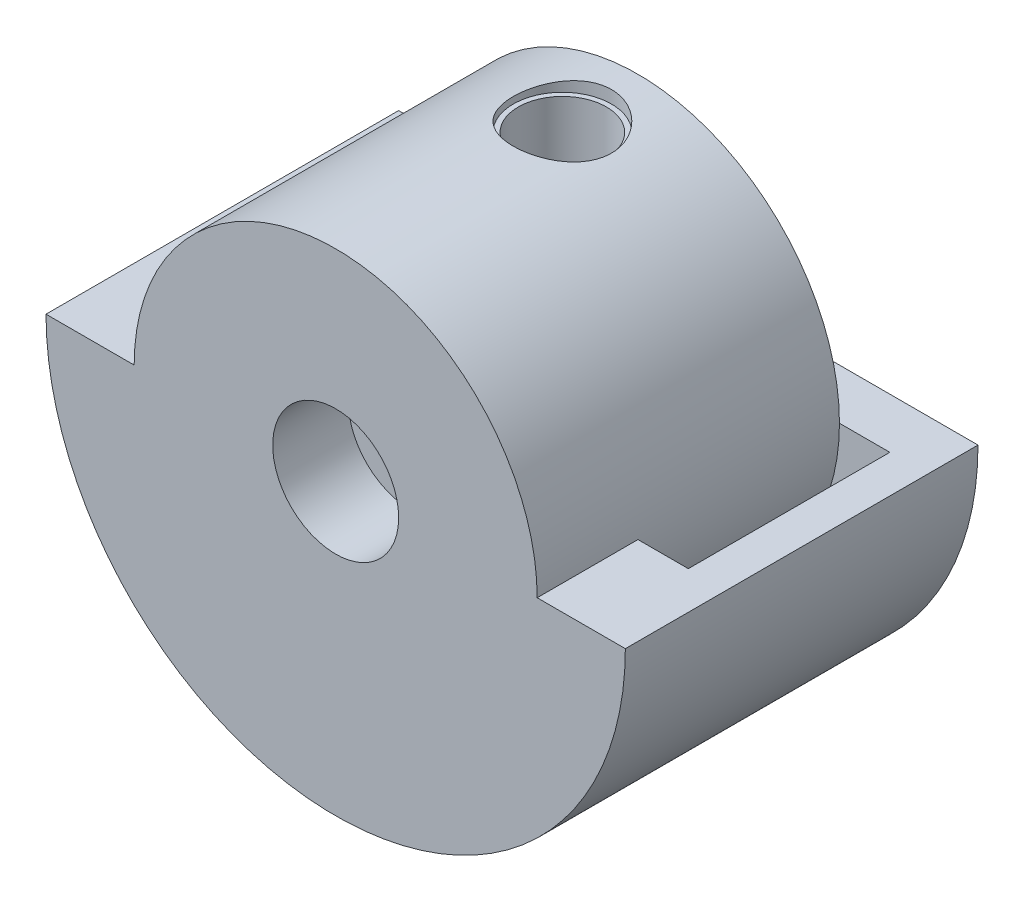
SolidWorks part; units mm, degrees
ref_plane "前视基准面" through (0, 0, 0) normal (0, 0, 1) x (1, 0, 0)
ref_plane "上视基准面" through (0, 0, 0) normal (0, 1, 0) x (1, 0, 0)
ref_plane "右视基准面" through (0, 0, 0) normal (1, 0, 0) x (0, 0, -1)
other "边界框"
ref_plane "Default Plane" through (-0.187, -7.4977, 0) normal (-0.6982, 0.7159, 0) x (0.7159, 0.6982, 0)
other "Configuration Table"
sketch "草图1" plane through (0, 0, 0) normal (0, 0, 1) x (1, 0, 0)
  line L0 (0, 0) -> (0.7723, 0) construction
  line L1 (0, 0) -> (0, 1.0561) construction
  circle A0 centre (0, 0) radius 2.5
  circle A1 centre (0, 0) radius 5
  dimension "D1" = 5
  dimension "D2" = 10
extrude "凸台-拉伸1" add sketch "草图1" along normal blind 6
sketch "草图2" plane through (0, 0, 0) normal (0, 0, 1) x (1, 0, 0)
  circle A0 centre (0, 0) radius 2.5 construction
  circle A1 centre (0, 0) radius 2.5
extrude "凸台-拉伸2" add sketch "草图2" along normal blind 3
sketch "草图3" plane through (0, 0, 0) normal (0, 0, 1) x (1, 0, 0)
  circle A0 centre (0, 0) radius 1.25
  dimension "D1" = 2.5
extrude "切除-拉伸3" cut sketch "草图3" along normal through all
sketch "草图8" plane through (0, 0, 6) normal (0, 0, 1) x (1, 0, 0)
  line L0 (-1016, 0) -> (-8, 0) construction
  line L1 (0, 0) -> (0, 7.0639) construction
  line L3 (8, 0) -> (1008.5412, 0) construction
  line L4 (-5, 0) -> (5, 0) construction
  circle A0 centre (0, 0) radius 8
  circle A1 centre (0, 0) radius 5 construction
  circle A2 centre (0, 0) radius 5
  dimension "D1" = 16
extrude "凸台-拉伸4" add sketch "草图8" against normal blind 12
ref_plane "基准面1" through (0, 8, 0) normal (0, 1, 0) x (1, 0, 0)
sketch "草图11" plane through (0, 8, 0) normal (0, 1, 0) x (1, 0, 0)
  line L0 (8, 6) -> (-8, 6) construction
  line L1 (0, 3.0864) -> (0, -9.1926) construction
  circle A0 centre (0, 3) radius 1.75
  dimension "D1" = 3.5
  dimension "D2" = 3
extrude "切除-拉伸4" cut sketch "草图11" against normal blind 12
sketch "草图12" plane through (0, 8, 0) normal (0, 1, 0) x (1, 0, 0)
  circle A2 centre (0, 3) radius 1.95
  circle A3 centre (0, 3) radius 1.95
  dimension "D1" = 0.2
extrude "切除-拉伸5" cut sketch "草图12" against normal blind 0.5
sketch "草图13" plane through (0, 0, 6) normal (0, 0, 1) x (1, 0, 0)
  line L0 (-8, 0) -> (-16, 0)
  line L1 (8, 0) -> (16, 0)
  circle A1 centre (0, 0) radius 8 construction
  circle A2 centre (0, 0) radius 16
  arc A3 (-16, 0) -> (16, 0) centre (0, 0) ccw
  arc A4 (-8, 0) -> (8, 0) centre (0, 0) ccw
  dimension "D1" = 8
extrude "凸台-拉伸5" add sketch "草图13" against normal blind 10
fillet "圆角1" radius 1 2 edges at (-16, 0, 1) (16, 0, 1)
sketch "草图15" plane through (0, 0, -4) normal (0, 0, -1) x (-1, 0, 0)
  line L0 (-10, 0) -> (-8, 0)
  line L1 (10, 0) -> (8, 0)
  arc A1 (-8, 0) -> (8, 0) centre (0, 0) ccw construction
  arc A2 (-10, 0) -> (10, 0) centre (0, 0) ccw
  arc A3 (-10, 0) -> (10, 0) centre (0, 0) ccw
  arc A4 (-8, 0) -> (8, 0) centre (0, 0) ccw
  dimension "D1" = 2
extrude "切除-拉伸7" cut sketch "草图15" against normal blind 6
sketch "草图16" plane through (0, 0, -4) normal (0, 0, -1) x (-1, 0, 0)
  line L0 (11.6613, 0) -> (14.9666, 0)
  line L1 (10, 0) -> (14.9666, 0) construction
  arc A0 (11.6613, 0) -> (7.1957, -14.2906) centre (-13.4375, 0) cw
  arc A1 (-15.9644, -1.0667) -> (15.9644, -1.0667) centre (0, 0) ccw construction
  arc A3 (7.1957, -14.2906) -> (15.9644, -1.0667) centre (0, 0) ccw
  arc A4 (15.9644, -1.0667) -> (14.9666, 0) centre (14.9666, -1) ccw construction
  arc A5 (15.9644, -1.0667) -> (14.9666, 0) centre (14.9666, -1) ccw
extrude "切除-拉伸8" cut sketch "草图16" against normal blind 10
fillet "圆角2" radius 10 1 edges at (-7.1957, -14.2906, 1)
sketch "草图17" plane through (0, 0, -4) normal (0, 0, -1) x (-1, 0, 0)
  line L0 (10, 0) -> (11.6613, 0) construction
  line L1 (-14.9666, 0) -> (-10, 0) construction
  line L2 (10, 0) -> (11.6613, 0)
  line L3 (-14.9666, 0) -> (-10, 0)
  arc A0 (9.6053, -9.9488) -> (11.6613, 0) centre (-13.4375, 0) ccw construction
  arc A1 (-10, 0) -> (10, 0) centre (0, 0) ccw construction
  arc A2 (-15.9644, -1.0667) -> (1.132, -15.9599) centre (0, 0) ccw construction
  arc A3 (-14.9666, 0) -> (-15.9644, -1.0667) centre (-14.9666, -1) ccw construction
  arc A4 (9.6053, -9.9488) -> (11.6613, 0) centre (-13.4375, 0) ccw
  arc A5 (-10, 0) -> (10, 0) centre (0, 0) ccw
  arc A6 (-15.9644, -1.0667) -> (1.132, -15.9599) centre (0, 0) ccw
  arc A7 (-14.9666, 0) -> (-15.9644, -1.0667) centre (-14.9666, -1) ccw
  arc A8 (1.132, -15.9599) -> (9.6053, -9.9488) centre (0.4245, -5.985) ccw construction
  arc A9 (1.132, -15.9599) -> (9.6053, -9.9488) centre (0.4245, -5.985) ccw
extrude "凸台-拉伸6" add sketch "草图17" along normal up to surface (2 mm away) up to face at (5, 0, -6)
sketch "草图18" plane through (0, 0, -6) normal (0, 0, -1) x (-1, 0, 0)
  line L0 (10, 0) -> (11.6613, 0) construction
  line L1 (-14.9666, 0) -> (-10, 0) construction
  line L2 (10, 0) -> (11.6613, 0)
  line L3 (-14.9666, 0) -> (-10, 0)
  line L4 (-8, 0) -> (-10, 0) construction
  line L5 (-8, 0) -> (-10, 0)
  line L6 (10, 0) -> (8, 0) construction
  line L7 (10, 0) -> (8, 0)
  line L8 (-8, 0) -> (-5, 0)
  line L9 (8, 0) -> (5, 0)
  arc A0 (9.6053, -9.9488) -> (11.6613, 0) centre (-13.4375, 0) ccw construction
  arc A1 (-15.9644, -1.0667) -> (1.132, -15.9599) centre (0, 0) ccw construction
  arc A2 (-14.9666, 0) -> (-15.9644, -1.0667) centre (-14.9666, -1) ccw construction
  arc A3 (9.6053, -9.9488) -> (11.6613, 0) centre (-13.4375, 0) ccw
  arc A4 (-15.9644, -1.0667) -> (1.132, -15.9599) centre (0, 0) ccw
  arc A5 (-14.9666, 0) -> (-15.9644, -1.0667) centre (-14.9666, -1) ccw
  arc A6 (1.132, -15.9599) -> (9.6053, -9.9488) centre (0.4245, -5.985) ccw construction
  arc A7 (1.132, -15.9599) -> (9.6053, -9.9488) centre (0.4245, -5.985) ccw
  circle A10 centre (0, 0) radius 5 construction
  arc A11 (-5, 0) -> (5, 0) centre (0, 0) ccw
extrude "凸台-拉伸7" add sketch "草图18" along normal blind 2
sketch "草图19" plane through (0, 0, -8) normal (0, 0, -1) x (-1, 0, 0)
  line L0 (11.6613, 0) -> (5, 0) construction
  line L1 (11.6613, 0) -> (11.5, 0)
  line L2 (-14.9666, 0) -> (-11.5, 0)
  arc A1 (-14.9666, 0) -> (-15.9644, -1.0667) centre (-14.9666, -1) ccw construction
  arc A2 (-11.5, 0) -> (11.5, 0) centre (0, 0) ccw
  arc A3 (-11.5, 0) -> (11.5, 0) centre (0, 0) ccw
  arc A4 (1.132, -15.9599) -> (9.6053, -9.9488) centre (0.4245, -5.985) ccw construction
  arc A5 (-15.9644, -1.0667) -> (1.132, -15.9599) centre (0, 0) ccw construction
  arc A6 (9.6053, -9.9488) -> (11.6613, 0) centre (-13.4375, 0) ccw construction
  arc A7 (-14.9666, 0) -> (-15.9644, -1.0667) centre (-14.9666, -1) ccw
  arc A8 (1.132, -15.9599) -> (9.6053, -9.9488) centre (0.4245, -5.985) ccw
  arc A9 (-15.9644, -1.0667) -> (1.132, -15.9599) centre (0, 0) ccw
  arc A10 (9.6053, -9.9488) -> (11.6613, 0) centre (-13.4375, 0) ccw
  dimension "D1" = 1.5
extrude "切除-拉伸9" cut sketch "草图19" against normal through all
sketch "草图20" plane through (0, 0, 0) normal (0, 0, -1) x (-1, 0, 0)
  circle A0 centre (0, 0) radius 5 construction
  arc A1 (5, 0) -> (-5, 0) centre (0, 0) ccw construction
  circle A6 centre (0, 0) radius 5
  arc A7 (5, 0) -> (-5, 0) centre (0, 0) ccw
  circle A8 centre (0, 0) radius 3.5
  circle M4 centre (0, 0) radius 5
  dimension "D1" = 1.5
extrude "凸台-拉伸8" add sketch "草图20" along normal up to surface (6 mm away) contours A6 A8 M4
sketch "草图21" plane through (0, 8, 0) normal (0, 1, 0) x (1, 0, 0)
  circle A0 centre (0, 3) radius 1.75 construction
  circle A1 centre (0, 3) radius 1.75
extrude "切除-拉伸10" cut sketch "草图21" against normal blind 10
